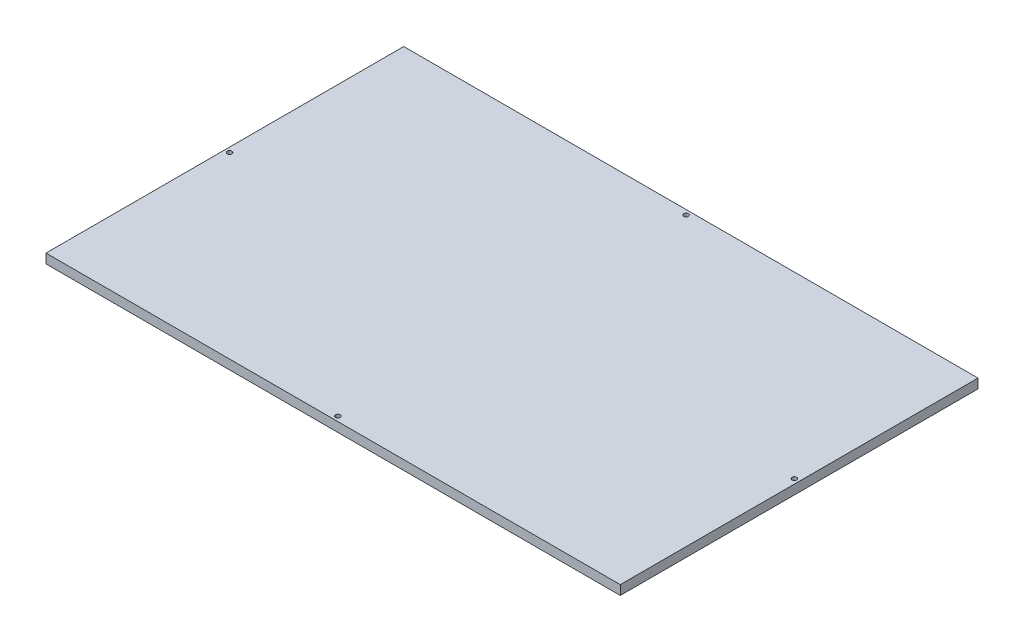
SolidWorks part; units mm, degrees
ref_plane "Front Plane" through (0, 0, 0) normal (0, 0, 1) x (1, 0, 0)
ref_plane "Top Plane" through (0, 0, 0) normal (0, 1, 0) x (1, 0, 0)
ref_plane "Right Plane" through (0, 0, 0) normal (1, 0, 0) x (0, 0, -1)
sketch "Sketch1" plane through (0, 0, 0) normal (0, 1, 0) x (1, 0, 0)
  line L1 (-305, 190) -> (305, 190)
  line L2 (-305, 190) -> (-305, -190)
  line L3 (-305, -190) -> (305, -190)
  line L4 (305, 190) -> (305, -190)
  line L5 (-305, 190) -> (305, -190) construction
  line L6 (-305, -190) -> (305, 190) construction
  point P0 (0, 0)
  dimension "D1" = 610
  dimension "D2" = 380
extrude "Boss-Extrude1" add sketch "Sketch1" along normal blind 10
sketch "Sketch2" plane through (0, 10, 0) normal (0, 1, 0) x (1, 0, 0)
  line L0 (305, 190) -> (-305, 190) construction
  line L1 (-305, 190) -> (-305, -190) construction
  line L2 (305, -190) -> (305, 190) construction
  line L3 (-305, -190) -> (305, -190) construction
  circle A0 centre (300, 0) radius 2.5
  circle A1 centre (0, 185) radius 2.5
  circle A2 centre (-300, 0) radius 2.5
  circle A3 centre (0, -185) radius 2.5
  dimension "D1" = 5
  dimension "D2" = 5
  dimension "D3" = 5
  dimension "D4" = 5
  dimension "D5" = 190
  dimension "D6" = 5
  dimension "D7" = 305
  dimension "D8" = 5
  dimension "D9" = 5
  dimension "D10" = 190
  dimension "D11" = 5
  dimension "D12" = 305
extrude "Cut-Extrude1" cut sketch "Sketch2" against normal blind 10
